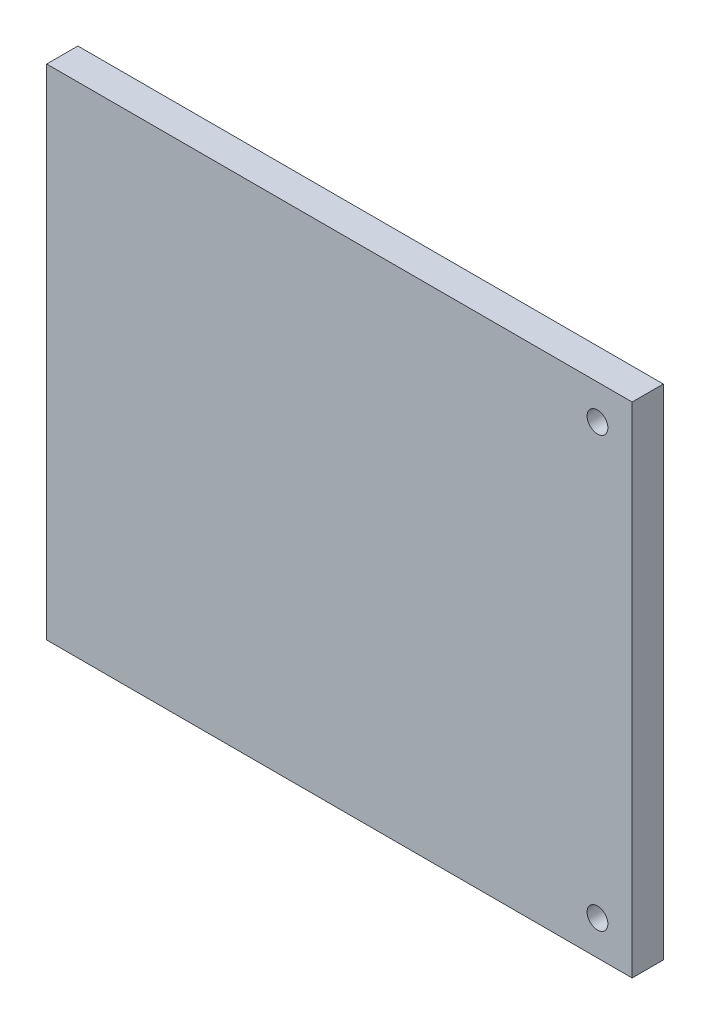
SolidWorks part; units mm, degrees
ref_plane "Front Plane" through (0, 0, 0) normal (0, 0, 1) x (1, 0, 0)
ref_plane "Top Plane" through (0, 0, 0) normal (0, 1, 0) x (1, 0, 0)
ref_plane "Right Plane" through (0, 0, 0) normal (1, 0, 0) x (0, 0, -1)
sketch "Sketch1" plane through (0, 0, 0) normal (0, 0, 1) x (1, 0, 0)
  line L1 (42.25, -36) -> (-42.25, -36)
  line L2 (42.25, -36) -> (42.25, 36)
  line L3 (42.25, 36) -> (-42.25, 36)
  line L4 (-42.25, -36) -> (-42.25, 36)
  line L5 (42.25, -36) -> (-42.25, 36) construction
  line L6 (42.25, 36) -> (-42.25, -36) construction
  point P0 (0, 0)
  dimension "D1" = 72
  dimension "D2" = 84.5
extrude "Boss-Extrude1" add sketch "Sketch1" along normal blind 4.5
sketch "Sketch2" plane through (0, 0, 0) normal (0, 0, -1) x (-1, 0, 0)
  line L0 (-42.25, -36) -> (-37.25, -36) construction
  line L1 (42.25, -36) -> (-42.25, -36) construction
  line L2 (-37.25, -36) -> (-37.25, -31) construction
  line L3 (-42.25, 36) -> (-37.25, 36) construction
  line L4 (-42.25, 36) -> (42.25, 36) construction
  line L5 (-37.25, 36) -> (-37.25, 31) construction
  circle A0 centre (-37.25, 31) radius 1.5
  circle A1 centre (-37.25, -31) radius 1.5
extrude "Cut-Extrude1" cut sketch "Sketch2" against normal through all
